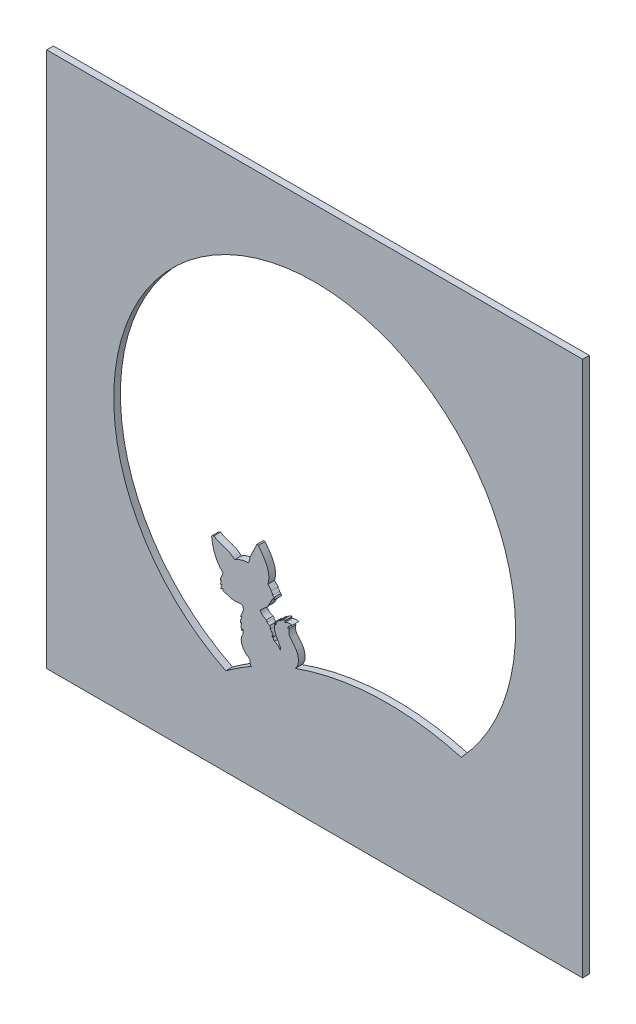
SolidWorks part; units mm, degrees
ref_plane "Plan de face" through (0, 0, 0) normal (0, 0, 1) x (1, 0, 0)
ref_plane "Plan de dessus" through (0, 0, 0) normal (0, 1, 0) x (1, 0, 0)
ref_plane "Plan de droite" through (0, 0, 0) normal (1, 0, 0) x (0, 0, -1)
sketch "Esquisse1" plane through (0, 0, 0) normal (0, 0, 1) x (1, 0, 0)
  line L1 (-200, 200) -> (200, 200)
  line L2 (-200, 200) -> (-200, -200)
  line L3 (-200, -200) -> (200, -200)
  line L4 (200, 200) -> (200, -200)
  line L5 (-200, 200) -> (200, -200) construction
  line L6 (-200, -200) -> (200, 200) construction
  circle A0 centre (0, 0) radius 150
  dimension "D1" = 300
  dimension "D2" = 400
extrude "Boss.-Extru.1" add sketch "Esquisse1" along normal blind 5
sketch "Esquisse2" plane through (0, 0, 5) normal (0, 0, 1) x (1, 0, 0)
  arc A0 (-66.2759, -134.5641) -> (109.4217, -102.6006) centre (54.5371, -299.781) cw
  circle A1 centre (0, 0) radius 150 construction
  arc A2 (-66.2759, -134.5641) -> (109.4217, -102.6006) centre (0, 0) ccw
  point P2 (109.4217, -102.6006)
  point P7 (0, 0)
extrude "Boss.-Extru.2" add sketch "Esquisse2" against normal up to vertex (5 mm away) up to point (200, -200, 0)
sketch "Esquisse5" plane through (0, 0, 5) normal (0, 0, 1) x (1, 0, 0)
  line L0 (-18.8663, -83.3519) -> (-20.3741, -83.7452)
  line L1 (-22.4609, -81.4229) -> (-21.6778, -79.5582)
  line L2 (-25.8225, -82.2621) -> (-25.8225, -81.4836)
  line L3 (-29.0538, -86.2596) -> (-29.4965, -84.4682)
  line L4 (-29.9741, -97.3592) -> (-32.1229, -94.4514)
  line L5 (-32.1229, -94.4514) -> (-30.5274, -94.7317)
  line L6 (-30.5274, -94.7317) -> (-31.8809, -92.6831)
  line L7 (-31.8809, -92.6831) -> (-33.497, -90.5383)
  line L8 (-33.497, -90.5383) -> (-32.5813, -90.5383)
  line L9 (-32.5813, -90.5383) -> (-33.6134, -89.007)
  line L10 (-33.6134, -89.007) -> (-36.2175, -87.523)
  line L11 (-36.2175, -87.523) -> (-34.9761, -87.3018)
  line L12 (-34.9761, -87.3018) -> (-36.0998, -86.512)
  line L13 (-30.9044, -70.4147) -> (-31.6469, -69.8779)
  line L14 (-31.6469, -69.8779) -> (-29.6095, -70.166)
  line L15 (-29.6095, -70.166) -> (-30.2374, -69.0282)
  line L16 (-30.2374, -69.0282) -> (-32.2495, -67.7558)
  line L17 (-32.2495, -67.7558) -> (-30.8411, -67.7558)
  line L18 (-30.8411, -67.7558) -> (-32.866, -66.116)
  line L19 (-32.866, -66.116) -> (-32.1229, -65.7058)
  line L20 (-32.1229, -65.7058) -> (-34.9761, -62.978)
  line L21 (-42.0317, -41.2942) -> (-43.1859, -41.2942)
  line L22 (-43.1859, -41.2942) -> (-44.0966, -43.2983)
  line L23 (-75.2317, -51.7835) -> (-76.6166, -52.3287)
  line L24 (-76.6166, -52.3287) -> (-76.9102, -52.9748)
  line L25 (-68.3034, -72.2012) -> (-70.4007, -77.2682)
  line L26 (-70.4007, -77.2682) -> (-70.4007, -78.0239)
  line L27 (-70.4007, -78.0239) -> (-69.5983, -77.8734)
  line L28 (-69.5983, -77.8734) -> (-70.2837, -80.2054)
  line L29 (-70.2837, -80.2054) -> (-70.2837, -80.8656)
  line L30 (-70.2837, -80.8656) -> (-69.0874, -80.2054)
  line L31 (-69.0874, -80.2054) -> (-69.7212, -81.8847)
  line L32 (-69.7212, -81.8847) -> (-69.7212, -83.2556)
  line L33 (-69.7212, -83.2556) -> (-68.1757, -82.1909)
  line L34 (-68.1757, -82.1909) -> (-68.4973, -83.7452)
  line L35 (-68.4973, -83.7452) -> (-67.9326, -83.9583)
  line L36 (-55.1896, -93.7736) -> (-54.1103, -93.3671)
  line L37 (-54.1103, -93.3671) -> (-55.1896, -95.9205)
  line L38 (-55.1896, -95.9205) -> (-55.1896, -98.0165)
  line L39 (-55.1896, -98.0165) -> (-54.6499, -97.4576)
  line L40 (-54.6499, -97.4576) -> (-54.9198, -99.9502)
  line L41 (-54.9198, -99.9502) -> (-54.6499, -102.6936)
  line L42 (-54.6499, -102.6936) -> (-53.5188, -101.0451)
  line L43 (-53.5188, -101.0451) -> (-53.5188, -104.785)
  line L44 (-50.1528, -117.0958) -> (-50.1528, -116.4584)
  line L45 (-50.1528, -116.4584) -> (-48.057, -118.5299)
  arc A0 (109.4217, -102.6006) -> (-66.2759, -134.5641) centre (54.5371, -299.781) ccw construction
  arc A1 (-47.0921, -122.1186) -> (-14.435, -107.0759) centre (54.5371, -299.781) cw
  spline S0 degree 3 poles (-14.435, -107.0759) (-11.1485, -103.5375) (-12.0001, -93.1831) (-20.6987, -88.2287) (-18.8663, -83.3519) knots 0 0 0 0 0.525388 1 1 1 1
  spline S1 degree 2 poles (-20.3741, -83.7452) (-18.8316, -81.7638) (-16.7359, -80.3692) knots 0 0 0 1 1 1
  spline S2 degree 2 poles (-16.7359, -80.3692) (-19.8024, -79.6158) (-22.4609, -81.4229) knots 0 0 0 1 1 1
  spline S3 degree 2 poles (-21.6778, -79.5582) (-24.2618, -80.1425) (-25.8225, -82.2621) knots 0 0 0 1 1 1
  spline S4 degree 2 poles (-25.8225, -81.4836) (-28.3513, -83.2595) (-29.0538, -86.2596) knots 0 0 0 1 1 1
  spline S5 degree 3 poles (-29.4965, -84.4682) (-30.3854, -86.7329) (-30.06, -91.4857) (-26.6584, -96.3538) (-25.1767, -99.7701) (-25.385, -101.3874) knots 0 0 0 0 0.40659 0.730892 1 1 1 1
  spline S6 degree 2 poles (-25.385, -101.3874) (-26.8024, -98.3754) (-29.9741, -97.3592) knots 0 0 0 1 1 1
  spline S7 degree 2 poles (-36.0998, -86.512) (-39.2172, -85.5579) (-40.6454, -82.599) knots 0 0 0 1 1 1
  spline S8 degree 3 poles (-40.6454, -82.599) (-39.0336, -80.6531) (-34.1812, -77.8509) (-32.8523, -72.3002) (-30.9044, -70.4147) knots 0 0 0 0 0.487449 1 1 1 1
  spline S9 degree 3 poles (-34.9761, -62.978) (-34.1027, -60.3941) (-33.7379, -52.1172) (-39.0561, -45.3456) (-42.0317, -41.2942) knots 0 0 0 0 0.34423 1 1 1 1
  spline S10 degree 3 poles (-44.0966, -43.2983) (-45.2312, -46.3383) (-48.3307, -50.269) (-48.8343, -55.0647) (-49.3766, -56.3763) knots 0 0 0 0 0.699336 1 1 1 1
  spline S11 degree 3 poles (-49.3766, -56.3763) (-53.035, -56.31) (-56.7179, -57.4293) (-59.7483, -59.4715) knots 0 0 0 0 1 1 1 1
  spline S12 degree 3 poles (-59.7483, -59.4715) (-61.7301, -57.3824) (-67.0241, -54.7808) (-72.7693, -53.5595) (-75.2317, -51.7835) knots 0 0 0 0 0.48679 1 1 1 1
  spline S13 degree 3 poles (-76.9102, -52.9748) (-76.1879, -60.0353) (-73.9462, -67.4045) (-68.3034, -72.2012) knots 0 0 0 0 1 1 1 1
  spline S14 degree 3 poles (-67.9326, -83.9583) (-65.8749, -84.4438) (-61.5589, -86.7288) (-56.654, -85.6854) (-54.2414, -85.6384) knots 0 0 0 0 0.460172 1 1 1 1
  spline S15 degree 3 poles (-54.2414, -85.6384) (-53.5503, -86.3981) (-52.6056, -89.4567) (-54.7371, -92.0369) (-55.1896, -93.7736) knots 0 0 0 0 0.354288 1 1 1 1
  spline S16 degree 3 poles (-53.5188, -104.785) (-54.7844, -106.3505) (-55.3931, -111.3885) (-52.2837, -115.4337) (-50.1528, -117.0958) knots 0 0 0 0 0.414653 1 1 1 1
  spline S17 degree 3 poles (-48.057, -118.5299) (-48.8594, -119.6985) (-48.3502, -121.5158) (-47.0921, -122.1186) knots 0 0 0 0 1 1 1 1
  point P9 (-22.4609, -81.4229)
  point P22 (-25.385, -101.3874)
  point P110 (0, 0)
  point P112 (0, 0)
  point P113 (0, 0)
  point P114 (0, 0)
  point P115 (0, 0)
  point P116 (0, 0)
  point P117 (-22.5562, -81.4836)
  point P118 (-25.3703, -101.5166)
  point P119 (-29.3547, -91.6511)
  point P120 (-29.9741, -86.2596)
  point P121 (0, 0)
  point P122 (-26.631, -96.78)
  point P123 (-27.2338, -98.8807)
  point P124 (-31.8809, -92.6831)
  point P125 (-32.2495, -94.4514)
extrude "Boss.-Extru.4" add sketch "Esquisse5" against normal up to vertex (5 mm away)
